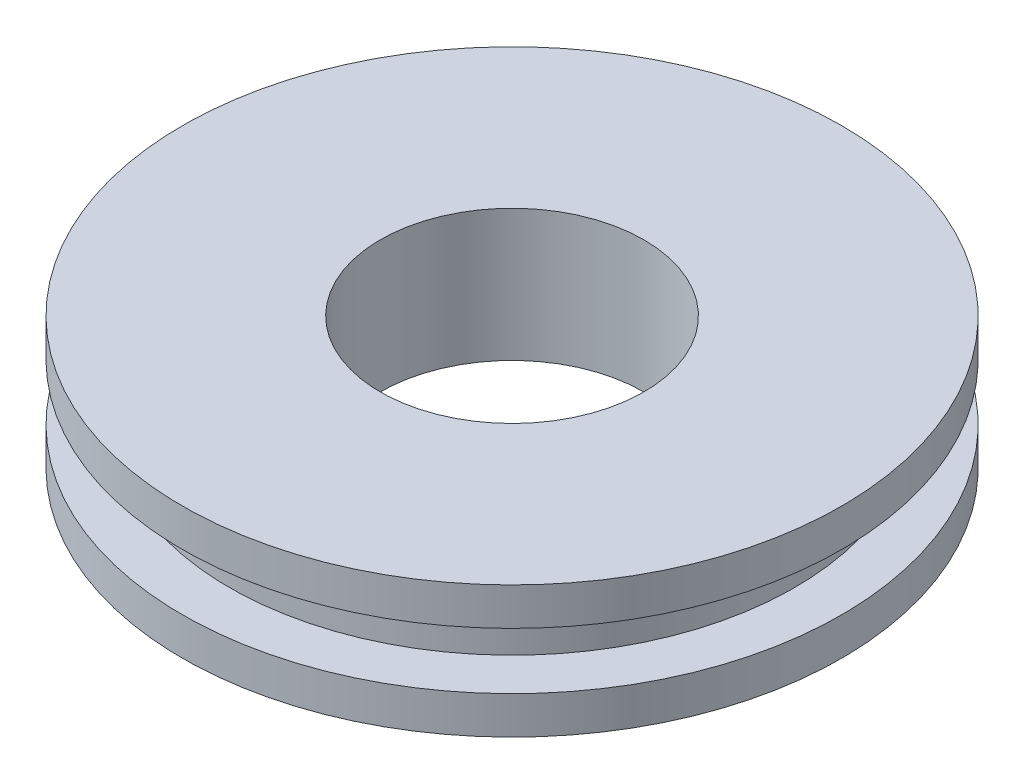
SolidWorks part; units mm, degrees
ref_plane "Front Plane" through (0, 0, 0) normal (0, 0, 1) x (1, 0, 0)
ref_plane "Top Plane" through (0, 0, 0) normal (0, 1, 0) x (1, 0, 0)
ref_plane "Right Plane" through (0, 0, 0) normal (1, 0, 0) x (0, 0, -1)
sketch "Sketch1" plane through (0, 0, 0) normal (0, 0, 1) x (1, 0, 0)
  line L2 (7, 3.5) -> (17.5, 3.5)
  line L3 (17.5, 3.5) -> (17.5, 1.5)
  line L4 (17.5, 1.5) -> (15, 1.5)
  line L5 (15, 1.5) -> (15, -1.5)
  line L6 (55, 0) -> (-55, 0) construction
  line L7 (17.5, -3.5) -> (17.5, -1.5)
  line L8 (17.5, -1.5) -> (15, -1.5)
  line L9 (7, -3.5) -> (17.5, -3.5)
  line L10 (7, 3.5) -> (7, -3.5)
  line L11 (0, 0) -> (0, 14.7507) construction
  point P4 (17.5, 2.5)
  point P8 (17.5, -2.5)
  point P14 (15, 0)
  dimension "D1" = 14
  dimension "D2" = 3
  dimension "D3" = 2
  dimension "D4" = 35
  dimension "D5" = 30
revolve "Revolve1" add sketch "Sketch1" angle 360 about L11
